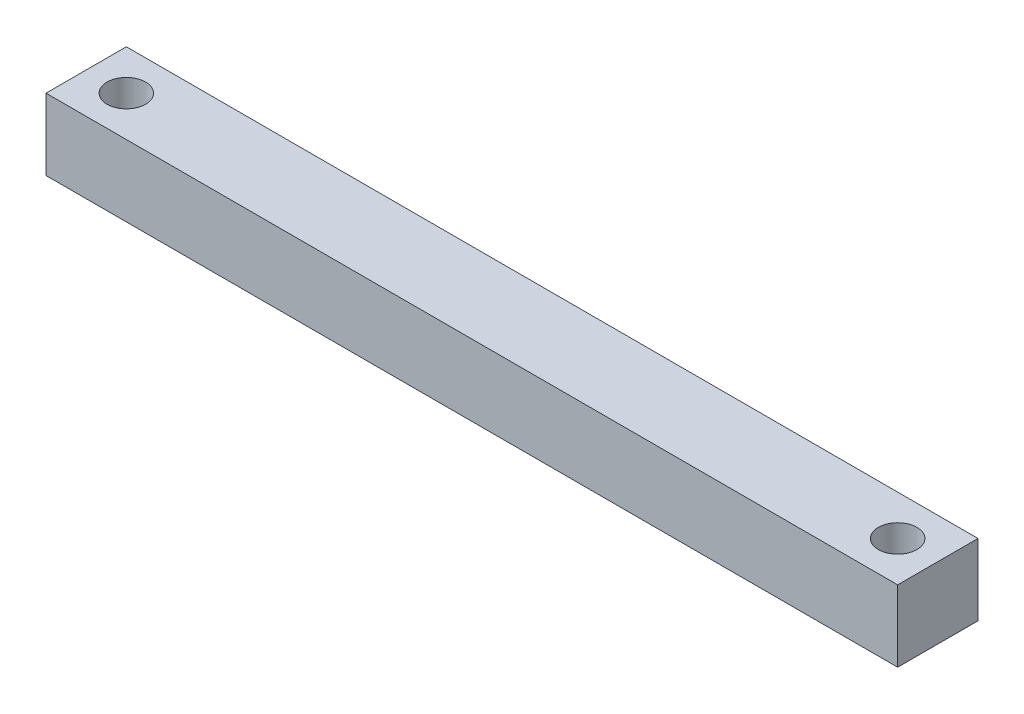
SolidWorks part; units mm, degrees
material "ASTM A36 Steel"
ref_plane "Front Plane" through (0, 0, 0) normal (0, 0, 1) x (1, 0, 0)
ref_plane "Top Plane" through (0, 0, 0) normal (0, 1, 0) x (1, 0, 0)
ref_plane "Right Plane" through (0, 0, 0) normal (1, 0, 0) x (0, 0, -1)
sketch "Sketch1" plane through (0, 0, 0) normal (0, 1, 0) x (1, 0, 0)
  line L1 (0, 0) -> (336.55, 0)
  line L2 (0, 0) -> (0, 31.75)
  line L3 (0, 31.75) -> (336.55, 31.75)
  line L4 (336.55, 0) -> (336.55, 31.75)
  circle A0 centre (15.875, 15.875) radius 7.62
  circle A1 centre (320.675, 15.875) radius 7.62
  dimension "D3" = 15.24
  dimension "D1" = 336.55
  dimension "D2" = 31.75
  dimension "D4" = 304.8
  dimension "D5" = 15.875
  dimension "D6" = 15.875
extrude "Boss-Extrude1" add sketch "Sketch1" along normal blind 28.194
sketch "Sketch2" plane through (0, 0, 0) normal (0, -1, 0) x (1, 0, 0)
  circle A0 centre (15.875, -15.875) radius 15.875
  circle A1 centre (320.675, -15.875) radius 15.875
  dimension "D1" = 31.75
sketch "Sketch3" plane through (0, 0, 0) normal (0, -1, 0) x (1, 0, 0)
  line L0 (336.55, -31.75) -> (0, -31.75) construction
  line L1 (152.4, -31.75) -> (184.15, -31.75)
  line L2 (152.4, -31.75) -> (152.4, 0)
  line L3 (152.4, 0) -> (184.15, 0)
  line L4 (184.15, -31.75) -> (184.15, 0)
  line L5 (0, 0) -> (336.55, 0) construction
  point P8 (168.275, -31.75)
  point P9 (168.275, -31.75)
split line "Split Line2"
split line "Split Line3"
equation "\"L\"= 12"
equation "\"D\"= .6"
equation "\"W\"= 1.25"
equation "\"Lo\"= \"L\" + \"W\""
equation "\"Th\"= 1.11'solved previously in mm and converted"
equation "\"D1@Sketch1\"=\"Lo\""
equation "\"D2@Sketch1\"=\"W\""
equation "\"D3@Sketch1\"=\"D\""
equation "\"D4@Sketch1\"=\"L\""
equation "\"D1@Boss-Extrude1\"=\"Th\""
